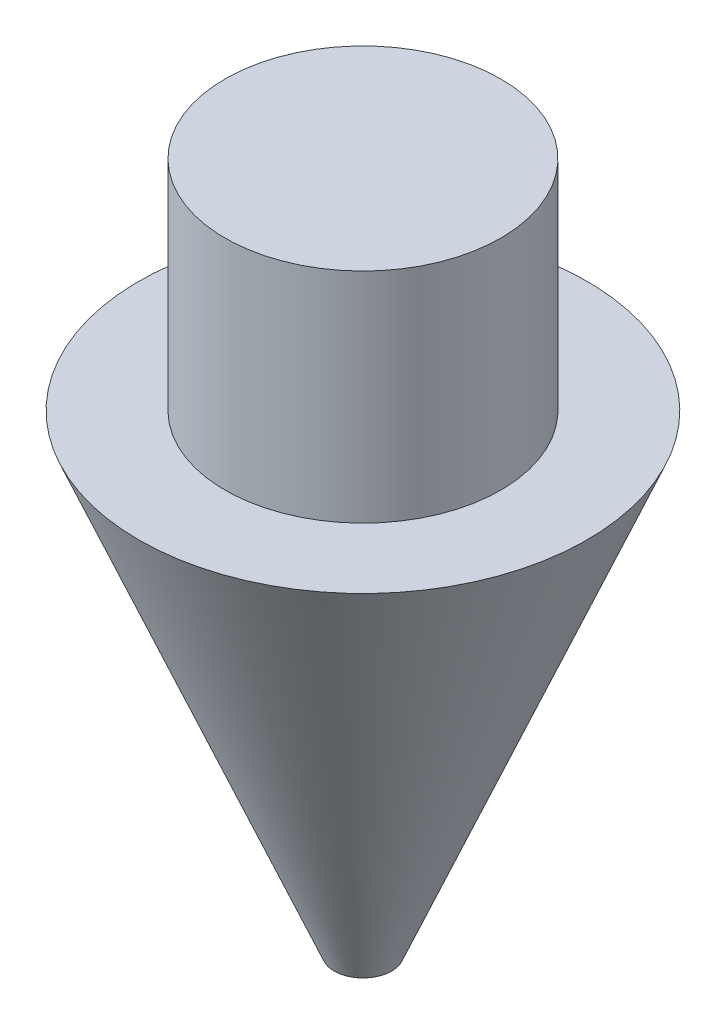
SolidWorks part; units mm, degrees
ref_plane "Ebene vorne" through (0, 0, 0) normal (0, 0, 1) x (1, 0, 0)
ref_plane "Ebene oben" through (0, 0, 0) normal (0, 1, 0) x (1, 0, 0)
ref_plane "Ebene rechts" through (0, 0, 0) normal (1, 0, 0) x (0, 0, -1)
sketch "Skizze1" plane through (0, 0, 0) normal (0, 0, 1) x (1, 0, 0)
  line L0 (0, 0) -> (2.4, 0)
  line L2 (55, 0) -> (-55, 0) construction
  line L3 (2.4, 0) -> (2.4, -3.8)
  line L4 (2.4, -3.8) -> (3.9, -3.8)
  line L7 (0, -55) -> (0, 55) construction
  line L8 (0, -12) -> (0, 0)
  line L10 (0, -12) -> (0.5, -12)
  line L11 (0.5, -12) -> (3.9, -3.8)
  dimension "D1" = 3.8
  dimension "D2" = 2.4
  dimension "D3" = 1.5
  dimension "D4" = 12
  dimension "D5" = 0.5
revolve "Rotation3" add sketch "Skizze1" angle 360 about L8
